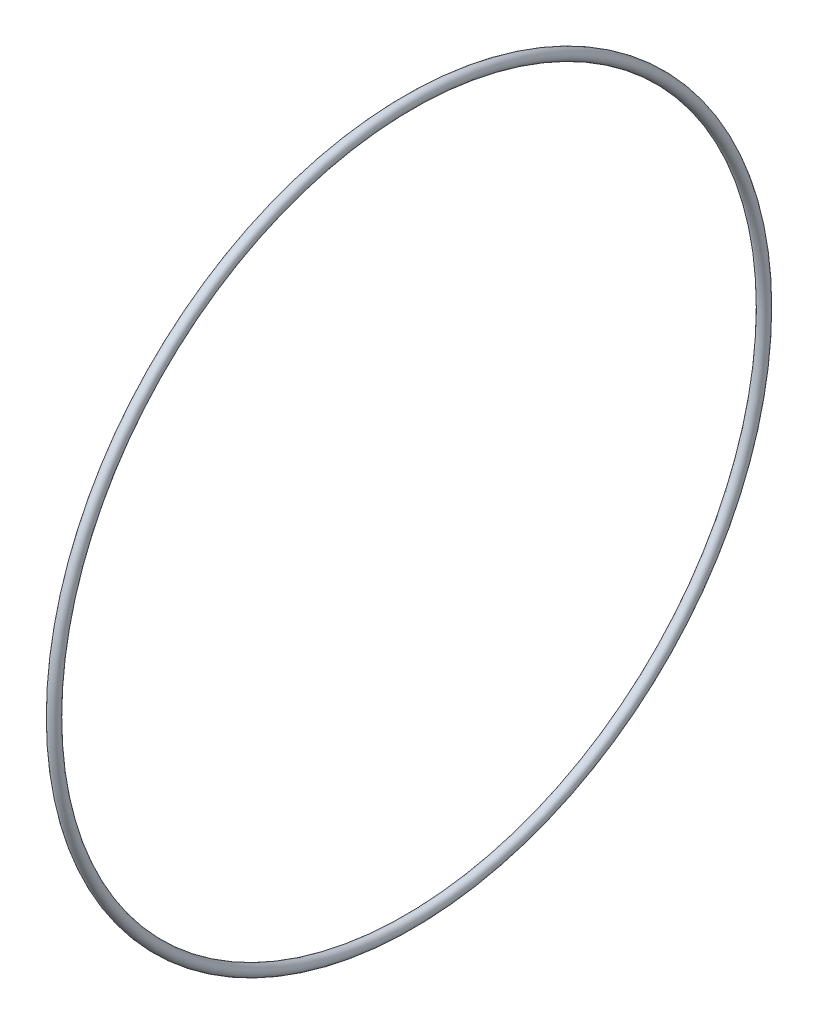
SolidWorks part; units mm, degrees
ref_plane "Alzado" through (0, 0, 0) normal (0, 0, 1) x (1, 0, 0)
ref_plane "Planta" through (0, 0, 0) normal (0, 1, 0) x (1, 0, 0)
ref_plane "Vista lateral" through (0, 0, 0) normal (1, 0, 0) x (0, 0, -1)
sketch "Croquis1" plane through (0, 0, 0) normal (0, 1, 0) x (1, 0, 0)
  line L0 (0, 0) -> (0, 16) construction
  line L1 (0, 16) -> (0, 16.25) construction
  line L2 (0, 0) -> (19.7867, 0) construction
  circle A0 centre (0, 16.25) radius 0.25
  dimension "D1" = 16
  dimension "D2" = 0.25
revolve "Revolución1" add sketch "Croquis1" angle 360 about L2
sketch "Croquis2" plane through (0, 0, 0) normal (1, 0, 0) x (0, 0, -1)
  circle A0 centre (0, 0) radius 15
  dimension "D1" = 30
